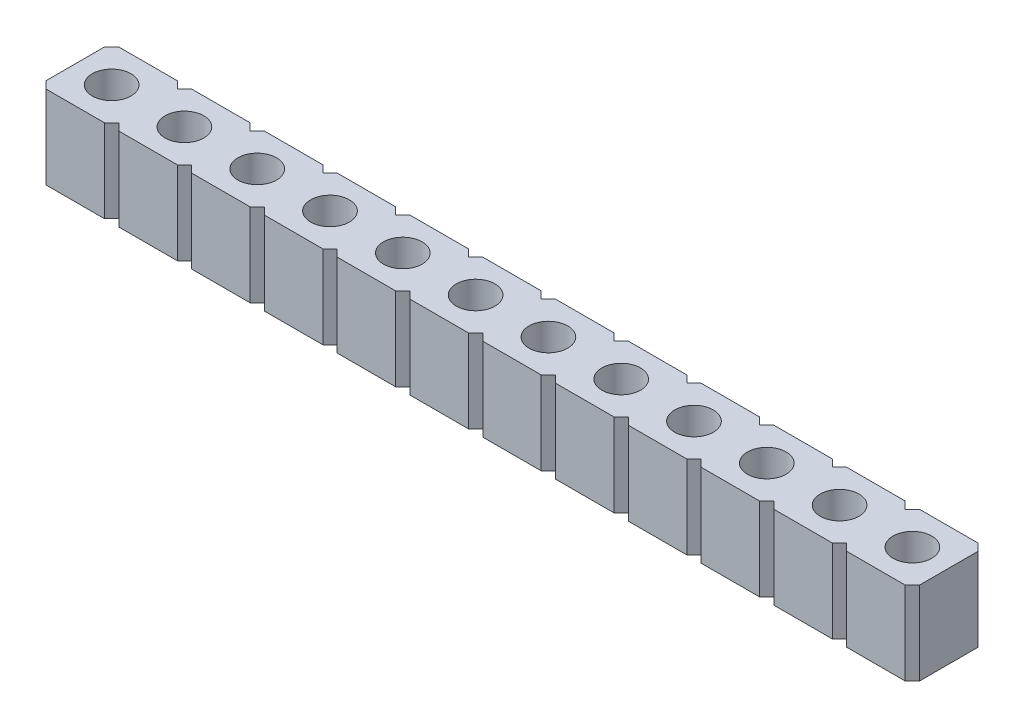
SolidWorks part; units mm, degrees
material "PA Type 6"
ref_plane "Front Plane" through (0, 0, 0) normal (0, 0, 1) x (1, 0, 0)
ref_plane "Top Plane" through (0, 0, 0) normal (0, 1, 0) x (1, 0, 0)
ref_plane "Right Plane" through (0, 0, 0) normal (1, 0, 0) x (0, 0, -1)
sketch "Sketch2" plane through (0, 0, 0) normal (0, 1, 0) x (1, 0, 0)
  line L0 (0, -55) -> (0, 55) construction
  line L1 (-1.02, 1.27) -> (1.02, 1.27)
  line L2 (-1.27, 1.02) -> (-1.27, -1.02)
  line L3 (-1.02, -1.27) -> (1.02, -1.27)
  line L4 (1.27, 1.02) -> (1.27, -1.02)
  line L5 (-55, 0) -> (55, 0) construction
  line L6 (1.02, 1.27) -> (1.27, 1.02)
  line L7 (-1.27, 1.02) -> (-1.02, 1.27)
  line L8 (-1.27, -1.02) -> (-1.02, -1.27)
  line L9 (1.02, -1.27) -> (1.27, -1.02)
  point P0 (-1.27, 1.27)
  point P1 (1.27, -1.27)
  point P2 (-1.27, -1.27)
  point P3 (1.27, 1.27)
  dimension "D1" = 2.54
  dimension "D2" = 1.27
  dimension "D3" = 2.54
  dimension "D4" = 1.27
extrude "Boss-Extrude1" add sketch "Sketch2" along normal blind 2.9
sketch "Sketch3" plane through (0, 2.9, 0) normal (0, 1, 0) x (1, 0, 0)
  circle A0 centre (0, 0) radius 0.675
  dimension "D1" = 1.35
extrude "Cut-Extrude1" cut sketch "Sketch3" against normal blind 3
sketch "Sketch4" plane through (0, 2.9, 0) normal (0, 1, 0) x (1, 0, 0)
  circle A0 centre (0, 0) radius 0.85
  dimension "D1" = 1.7
pattern_linear "LPattern1" count 12 spacing 2.54 along (1, 0, 0) of "Boss-Extrude1", "Cut-Extrude1"
